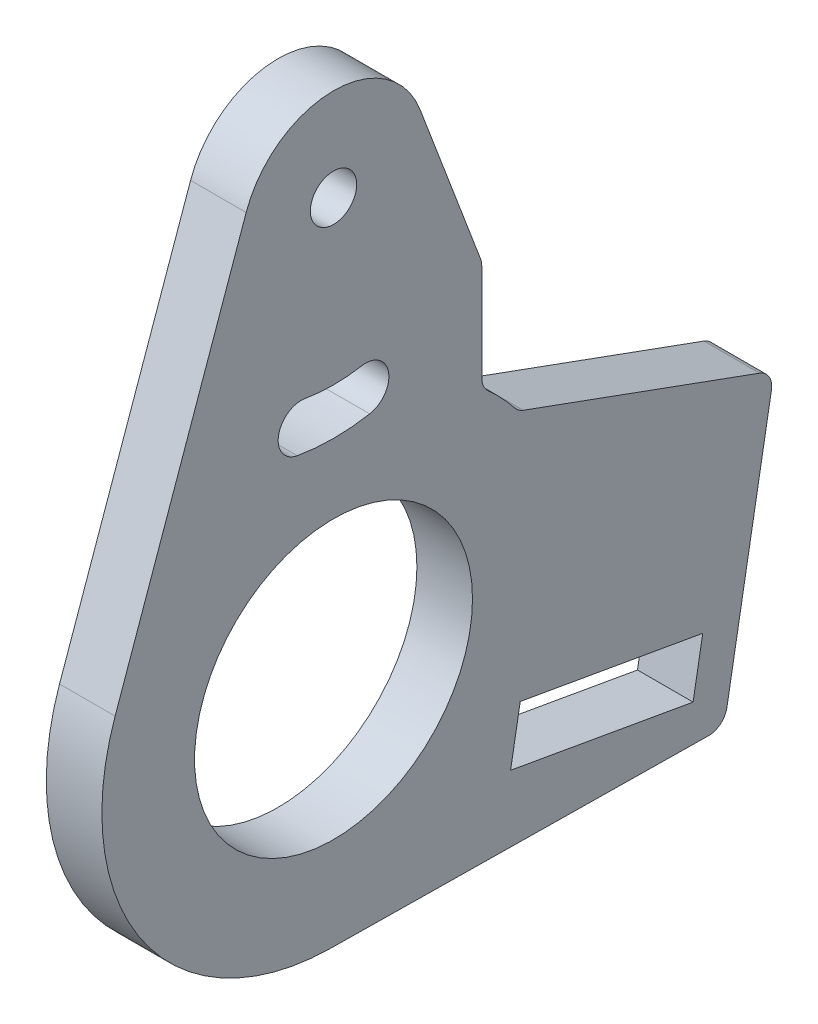
SolidWorks part; units mm, degrees
ref_plane "Front Plane" through (0, 0, 0) normal (0, 0, 1) x (1, 0, 0)
ref_plane "Top Plane" through (0, 0, 0) normal (0, 1, 0) x (1, 0, 0)
ref_plane "Right Plane" through (0, 0, 0) normal (1, 0, 0) x (0, 0, -1)
sketch "Sketch1" plane through (0, 0, 0) normal (1, 0, 0) x (0, 0, -1)
  line L5 (-50, 15) -> (-50, -5) construction
  line L7 (-59.4281, 18.3333) -> (-73.5702, -21.6667)
  line L9 (-29.8481, -42.1635) -> (-10.1519, -45.6365)
  line L17 (-10.1519, -45.6365) -> (-11.1938, -51.5453)
  line L21 (-20, -5) -> (-20, -43.9) construction
  line L23 (-11.1938, -51.5453) -> (-30.89, -48.0724)
  line L24 (-30.89, -48.0724) -> (-29.8481, -42.1635)
  line L25 (-22.6556, -13.3481) -> (-3.8618, -20.1885) construction
  line L26 (-10.6729, -48.5909) -> (-6.7336, -49.2855) construction
  line L28 (-50.3221, -54.9979) -> (-7.8374, -55.5453)
  line L31 (-34, 1) -> (-40.649, 18.544)
  line L34 (-34, -10.7906) -> (-34, 1)
  line L36 (-30, -5) -> (-10, -5) construction
  line L37 (-10, -5) -> (-10, 0) construction
  line L38 (-10, 0) -> (-30, 0) construction
  line L39 (-30, 0) -> (-30, -5) construction
  line L40 (-20.9455, -8.6496) -> (-22.6556, -13.3481) construction
  line L41 (-22.6556, -13.3481) -> (-3.8618, -20.1885) construction
  line L42 (-3.8618, -20.1885) -> (-2.1517, -15.49) construction
  line L43 (-2.1517, -15.49) -> (-20.9455, -8.6496) construction
  line L44 (-30, -5) -> (-50, -30) construction
  line L45 (-50, -30) -> (-22.6556, -13.3481) construction
  line L46 (-30.071, -14.9058) -> (-2.4446, -24.961)
  line L47 (-7.8374, -55.5453) -> (-2.4446, -24.961)
  circle A0 centre (-50, -30) radius 15
  circle A2 centre (-50, 15) radius 2.5
  arc A3 (-55.903, -4.109) -> (-44.097, -4.109) centre (-50, 15) ccw construction
  arc A4 (-53.0388, -2.2341) -> (-53.9071, -7.1582) centre (-53.473, -4.6962) ccw
  arc A5 (-46.0929, -7.1582) -> (-46.9612, -2.2341) centre (-46.527, -4.6962) ccw
  arc A6 (-53.9071, -7.1582) -> (-46.0929, -7.1582) centre (-50, 15) ccw
  arc A7 (-53.0388, -2.2341) -> (-46.9612, -2.2341) centre (-50, 15) ccw
  arc A8 (-40.649, 18.544) -> (-59.4281, 18.3333) centre (-50, 15) ccw
  arc A9 (-73.5702, -21.6667) -> (-50.3221, -54.9979) centre (-50, -30) ccw
  arc A10 (-34, -10.7906) -> (-30.071, -14.9058) centre (-50, -30) cw
  point P17 (-20, -5)
  point P37 (-20, -5)
  dimension "D3" = 5
  dimension "D7" = 30
  dimension "D8" = 7.5
  dimension "D6" = 10
  dimension "D1" = 20
  dimension "D2" = 20
  dimension "D4" = 50
  dimension "D5" = 30
  dimension "D9" = 25
  dimension "D10" = 5
  dimension "D11" = 4
  dimension "D12" = 6
  dimension "D13" = 20
  dimension "D14" = 38.9
  dimension "D15" = 4
  dimension "D16" = 100
  dimension "D17" = 4
  dimension "D18" = 6
  dimension "D19" = 20
  dimension "D20" = 20
  dimension "D21" = 4
  dimension "D22" = 20
extrude "Boss-Extrude1" add sketch "Sketch1" along normal blind 6
fillet "Fillet1" radius 2 5 edges at (3, 1, 34) (3, -10.7906, 34) (3, -14.9058, 30.071) (3, -55.5453, 7.8374) (3, -24.961, 2.4446)
